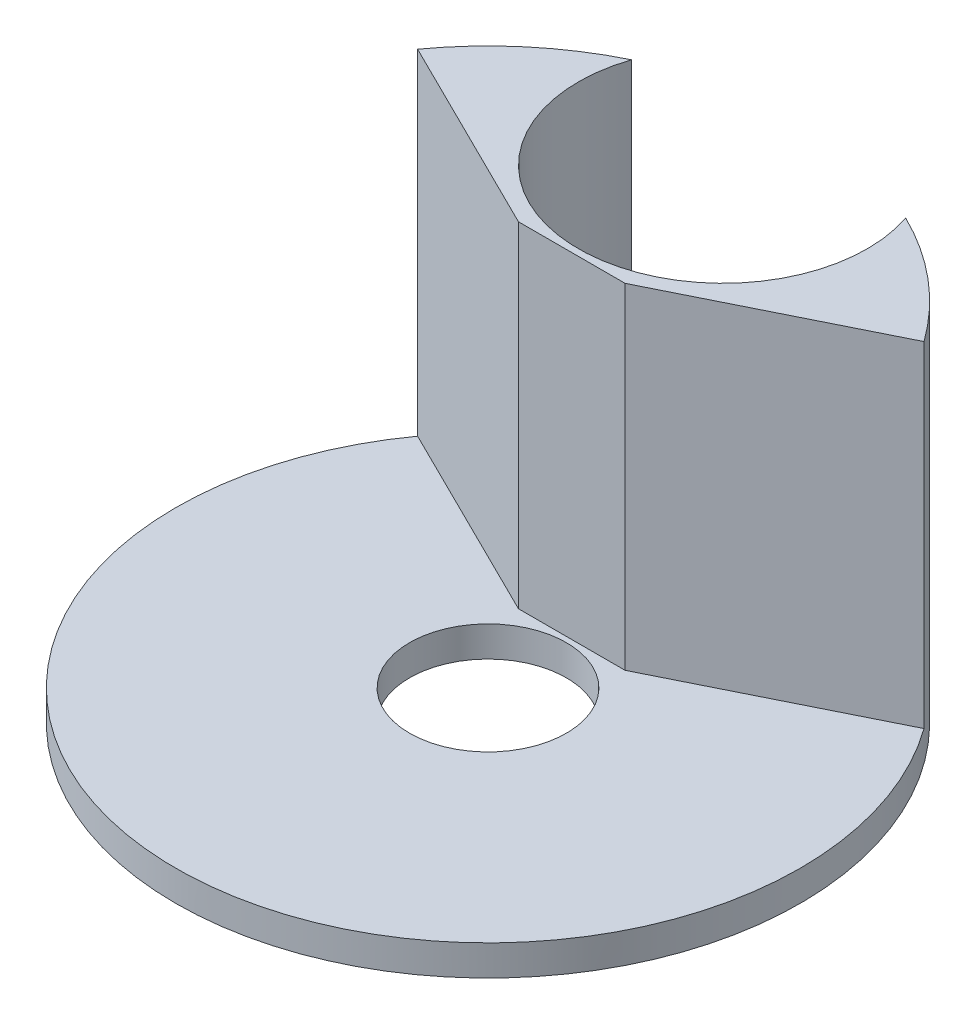
SolidWorks part; units mm, degrees
ref_plane "Front Plane" through (0, 0, 0) normal (0, 0, 1) x (1, 0, 0)
ref_plane "Top Plane" through (0, 0, 0) normal (0, 1, 0) x (1, 0, 0)
ref_plane "Right Plane" through (0, 0, 0) normal (1, 0, 0) x (0, 0, -1)
sketch "Sketch1" plane through (0, 0, 0) normal (0, 1, 0) x (1, 0, 0)
  circle A0 centre (0, 0) radius 20.5
  dimension "D1" = 41
extrude "Boss-Extrude1" add sketch "Sketch1" along normal blind 2
sketch "Sketch2" plane through (0, 2, 0) normal (0, 1, 0) x (1, 0, 0)
  circle A0 centre (0, 0) radius 5.15
  dimension "D1" = 10.3
extrude "Cut-Extrude1" cut sketch "Sketch2" against normal blind 3
sketch "Sketch3" plane through (0, 2, 0) normal (0, 1, 0) x (1, 0, 0)
  circle A0 centre (0, 13) radius 6.5
  dimension "D2" = 13
  dimension "D1" = 13
extrude "Cut-Extrude2" cut sketch "Sketch3" against normal blind 2
sketch "Sketch4" plane through (0, 2, 0) normal (0, 1, 0) x (1, 0, 0)
  line L0 (-3.5, 5.5) -> (-16.6208, 12)
  line L1 (3.5, 5.5) -> (16.6208, 12)
  line L4 (-3.5, 5.5) -> (3.5, 5.5)
  arc A0 (-16.6208, 12) -> (-9, 18.4187) centre (0, 0) cw
  circle A1 centre (0, 0) radius 20.5 construction
  arc A4 (9, 18.4187) -> (16.6208, 12) centre (0, 0) cw
  arc A6 (-9, 18.4187) -> (9, 18.4187) centre (0, 15.4184) ccw
  dimension "D1" = 12
  dimension "D2" = 12
  dimension "D3" = 5.5
  dimension "D4" = 5.5
  dimension "D5" = 3.5
  dimension "D6" = 3.5
  dimension "D7" = 9
  dimension "D8" = 9
extrude "Boss-Extrude4" add sketch "Sketch4" along normal blind 22
